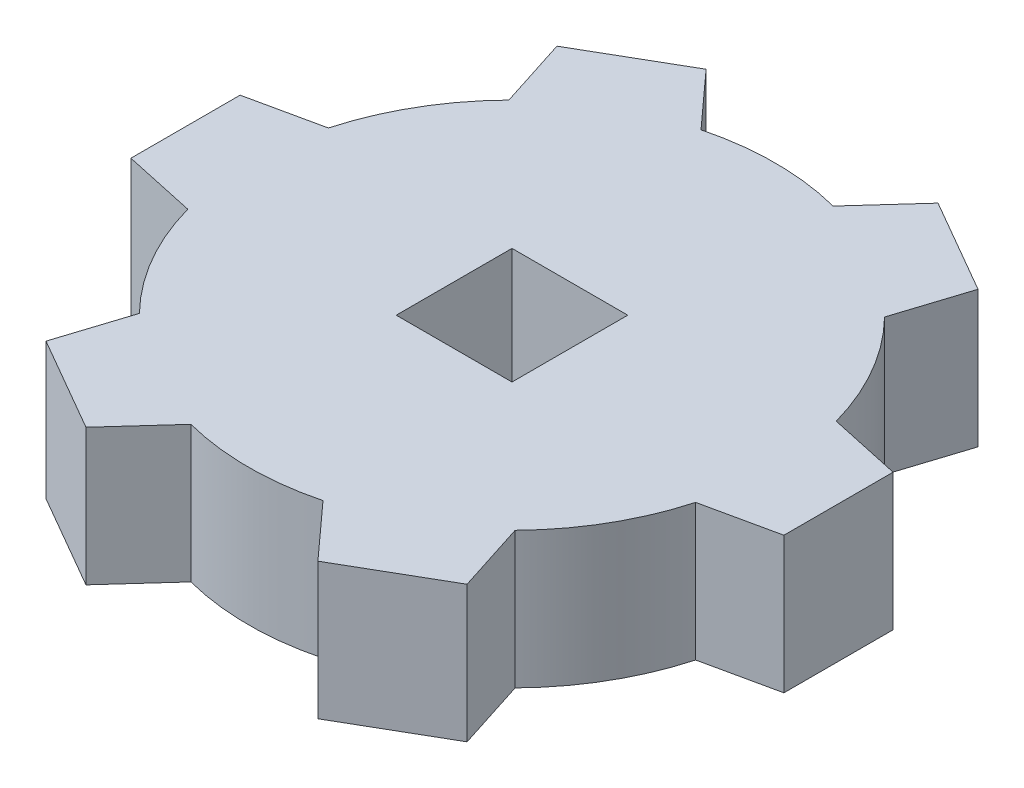
SolidWorks part; units mm, degrees
ref_plane "Front Plane" through (0, 0, 0) normal (0, 0, 1) x (1, 0, 0)
ref_plane "Top Plane" through (0, 0, 0) normal (0, 1, 0) x (1, 0, 0)
ref_plane "Right Plane" through (0, 0, 0) normal (1, 0, 0) x (0, 0, -1)
sketch "Sketch2" plane through (0, 0, 0) normal (0, 1, 0) x (1, 0, 0)
  line L0 (0, 0) -> (12.1833, 0) construction
  line L1 (9.65, 0) -> (9.65, -2.0552) construction
  line L2 (9.65, -2.0552) -> (9.65, 2.0284) construction
  line L3 (7.7116, -9.3569) -> (4.2475, -11.3569)
  line L4 (11.9592, 2) -> (11.9592, -2)
  line L5 (11.9592, 2) -> (9.65, 2.5)
  line L6 (11.9592, -2) -> (9.65, -2.5)
  line L7 (9.65, -2.5) -> (9.2999, -2.5758)
  line L8 (9.65, 2.5) -> (9.2999, 2.5758)
  line L9 (7.7116, -9.3569) -> (6.9901, -7.1071)
  line L10 (4.2475, -11.3569) -> (2.6599, -9.6071)
  line L11 (2.6599, -9.6071) -> (2.4192, -9.3418)
  line L12 (6.9901, -7.1071) -> (6.8807, -6.766)
  line L13 (4.825, -8.3571) -> (3.0451, -9.3848) construction
  line L14 (3.0451, -9.3848) -> (6.5817, -7.3429) construction
  line L15 (-4.2475, -11.3569) -> (-7.7116, -9.3569)
  line L16 (-4.2475, -11.3569) -> (-2.6599, -9.6071)
  line L17 (-7.7116, -9.3569) -> (-6.9901, -7.1071)
  line L18 (-6.9901, -7.1071) -> (-6.8807, -6.766)
  line L19 (-2.6599, -9.6071) -> (-2.4192, -9.3418)
  line L20 (-4.825, -8.3571) -> (-6.6049, -7.3295) construction
  line L21 (-6.6049, -7.3295) -> (-3.0683, -9.3714) construction
  line L22 (-11.9592, -2) -> (-11.9592, 2)
  line L23 (-11.9592, -2) -> (-9.65, -2.5)
  line L24 (-11.9592, 2) -> (-9.65, 2.5)
  line L25 (-9.65, 2.5) -> (-9.2999, 2.5758)
  line L26 (-9.65, -2.5) -> (-9.2999, -2.5758)
  line L27 (-9.65, 0) -> (-9.65, 2.0552) construction
  line L28 (-9.65, 2.0552) -> (-9.65, -2.0284) construction
  line L29 (-7.7116, 9.3569) -> (-4.2475, 11.3569)
  line L30 (-7.7116, 9.3569) -> (-6.9901, 7.1071)
  line L31 (-4.2475, 11.3569) -> (-2.6599, 9.6071)
  line L32 (-2.6599, 9.6071) -> (-2.4192, 9.3418)
  line L33 (-6.9901, 7.1071) -> (-6.8807, 6.766)
  line L34 (-4.825, 8.3571) -> (-3.0451, 9.3848) construction
  line L35 (-3.0451, 9.3848) -> (-6.5817, 7.3429) construction
  line L36 (4.2475, 11.3569) -> (7.7116, 9.3569)
  line L37 (4.2475, 11.3569) -> (2.6599, 9.6071)
  line L38 (7.7116, 9.3569) -> (6.9901, 7.1071)
  line L39 (6.9901, 7.1071) -> (6.8807, 6.766)
  line L40 (2.6599, 9.6071) -> (2.4192, 9.3418)
  line L41 (4.825, 8.3571) -> (6.6049, 7.3295) construction
  line L42 (6.6049, 7.3295) -> (3.0683, 9.3714) construction
  line L44 (2.12, 2.12) -> (-2.12, 2.12)
  line L45 (2.12, 2.12) -> (2.12, -2.12)
  line L46 (2.12, -2.12) -> (-2.12, -2.12)
  line L47 (-2.12, 2.12) -> (-2.12, -2.12)
  line L48 (2.12, 2.12) -> (-2.12, -2.12) construction
  line L49 (2.12, -2.12) -> (-2.12, 2.12) construction
  arc A0 (9.2999, 2.5758) -> (6.8807, 6.766) centre (0, 0) ccw
  arc A1 (2.4192, 9.3418) -> (-2.4192, 9.3418) centre (0, 0) ccw
  arc A2 (-6.8807, 6.766) -> (-9.2999, 2.5758) centre (0, 0) ccw
  arc A3 (-9.2999, -2.5758) -> (-6.8807, -6.766) centre (0, 0) ccw
  arc A4 (-2.4192, -9.3418) -> (2.4192, -9.3418) centre (0, 0) ccw
  arc A5 (6.8807, -6.766) -> (9.2999, -2.5758) centre (0, 0) ccw
  point P60 (0, 0)
  dimension "D1" = 19.3
  dimension "D2" = 5
  dimension "D3" = 4
  dimension "D5" = 4.24
  dimension "D6" = 4.24
  dimension "D4" = 6
extrude "Boss-Extrude1" add sketch "Sketch2" along normal blind 5
